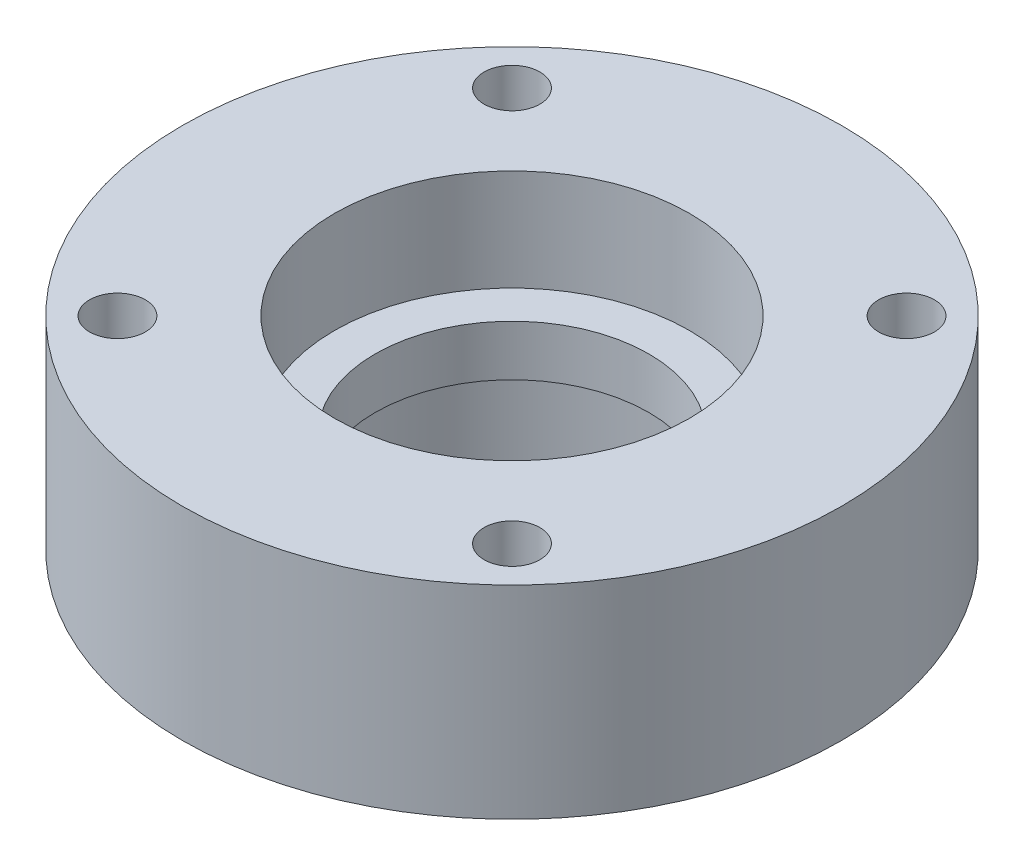
SolidWorks part; units mm, degrees
material "Д16Т ГОСТ 4784-74"
ref_plane "Спереди" through (0, 0, 0) normal (0, 0, 1) x (1, 0, 0)
ref_plane "Сверху" through (0, 0, 0) normal (0, 1, 0) x (1, 0, 0)
ref_plane "Справа" through (0, 0, 0) normal (1, 0, 0) x (0, 0, -1)
sketch "Эскиз1" plane through (0, 0, 0) normal (0, 0, 1) x (1, 0, 0)
  line L0 (0, 0) -> (0, 58.1583) construction
  line L1 (13.5, 5) -> (13.5, 0)
  line L2 (13.5, 0) -> (17.5, 0)
  line L3 (32.5, -5) -> (32.5, 15)
  line L4 (32.5, 15) -> (17.5, 15)
  line L5 (17.5, 15) -> (17.5, 5)
  line L6 (17.5, 5) -> (13.5, 5)
  line L7 (17.5, 0) -> (17.5, -10)
  line L8 (17.5, -10) -> (22.5, -10)
  line L9 (22.5, -10) -> (22.5, -5)
  line L10 (22.5, -5) -> (32.5, -5)
  dimension "D1" = 10
  dimension "D2" = 5
  dimension "D3" = 35
  dimension "D4" = 27
  dimension "D5" = 65
  dimension "D6" = 5
  dimension "D7" = 5
  dimension "D8" = 10
revolve "Повернуть1" add sketch "Эскиз1" angle 360 about L0
hole_wizard "Отверстие с зазором M51" positions "Эскиз3" profile "Эскиз2" hole size "M5" standard "DIN" end condition through all
sketch "Эскиз3" plane through (0, 15, 0) normal (0, 1, 0) x (-1, 0, 0)
  line L1 (19.4454, -19.4454) -> (-19.4454, -19.4454)
  line L2 (19.4454, -19.4454) -> (19.4454, 19.4454)
  line L3 (19.4454, 19.4454) -> (-19.4454, 19.4454)
  line L4 (-19.4454, -19.4454) -> (-19.4454, 19.4454)
  circle A0 centre (0, 0) radius 27.5
  point P0 (19.4454, 19.4454)
  point P38 (19.4454, -19.4454)
  point P40 (-19.4454, -19.4454)
  point P42 (-19.4454, 19.4454)
  dimension "D1" = 55
sketch "Эскиз2" plane through (-19.4454, 15, 19.4454) normal (1, 0, 0) x (0, 0, 1)
  line L0 (0, 0) -> (0, 25)
  line L1 (0, 25) -> (2.75, 25)
  line L2 (2.75, 25) -> (2.75, 0)
  line L5 (2.75, 0) -> (0, 0)
  line L11 (0, -6.35) -> (0, 107.95) construction
  dimension "Диаметр сквозного отверстия" = 5.5
  dimension "Глубина сквозного отверстия" = 25
sketch "Эскиз4" plane through (0, -5, 0) normal (0, -1, 0) x (1, 0, 0)
  circle A0 centre (0, 0) radius 27.5
  dimension "D1" = 55
